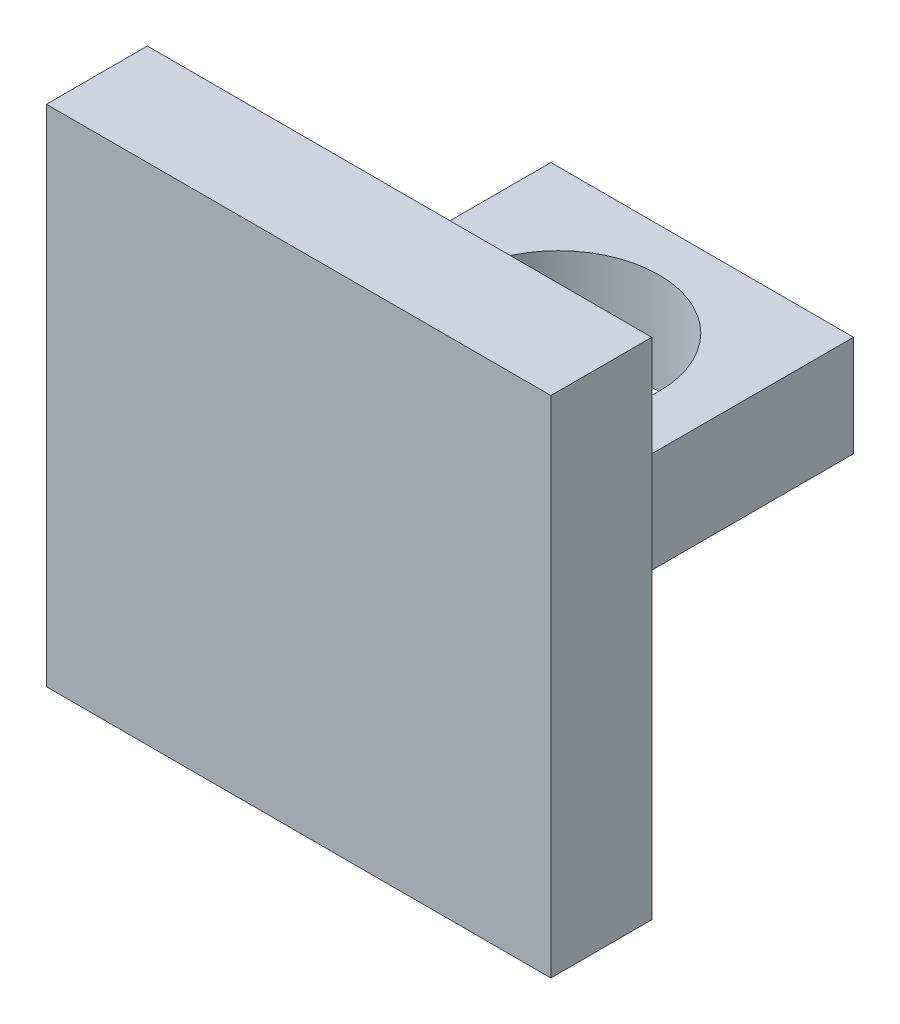
SolidWorks part; units mm, degrees
material "橡胶"
ref_plane "前视基准面" through (0, 0, 0) normal (0, 0, 1) x (1, 0, 0)
ref_plane "上视基准面" through (0, 0, 0) normal (0, 1, 0) x (1, 0, 0)
ref_plane "右视基准面" through (0, 0, 0) normal (1, 0, 0) x (0, 0, -1)
sketch "草图1" plane through (0, 0, 0) normal (0, 0, 1) x (1, 0, 0)
  line L1 (25, -25) -> (-25, -25)
  line L2 (25, -25) -> (25, 25)
  line L3 (25, 25) -> (-25, 25)
  line L4 (-25, -25) -> (-25, 25)
  line L5 (25, -25) -> (-25, 25) construction
  line L6 (25, 25) -> (-25, -25) construction
  point P0 (0, 0)
  dimension "D1" = 50
  dimension "D2" = 50
extrude "凸台-拉伸1" add sketch "草图1" along normal blind 10
sketch "草图2" plane through (0, 0, 0) normal (0, 0, -1) x (-1, 0, 0)
  line L1 (15, -5) -> (-15, -5)
  line L2 (15, -5) -> (15, 5)
  line L3 (15, 5) -> (-15, 5)
  line L4 (-15, -5) -> (-15, 5)
  line L5 (15, -5) -> (-15, 5) construction
  line L6 (15, 5) -> (-15, -5) construction
  point P0 (0, 0)
  dimension "D1" = 30
  dimension "D2" = 10
extrude "凸台-拉伸2" add sketch "草图2" along normal blind 30
sketch "草图3" plane through (0, 5, 0) normal (0, 1, 0) x (1, 0, 0)
  circle A0 centre (0, 15.7171) radius 10
extrude "切除-拉伸1" cut sketch "草图3" against normal blind 30
